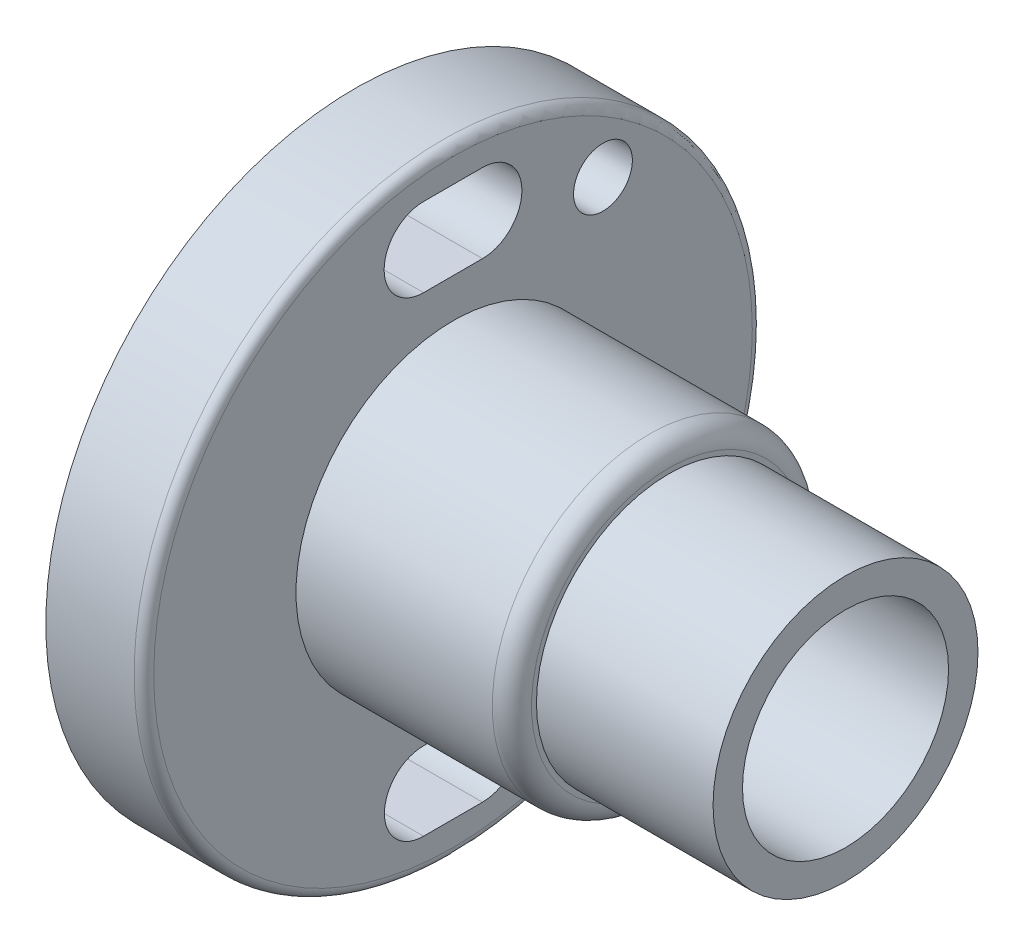
SolidWorks part; units mm, degrees
ref_plane "Front Plane" through (0, 0, 0) normal (0, 0, 1) x (1, 0, 0)
ref_plane "Top Plane" through (0, 0, 0) normal (0, 1, 0) x (1, 0, 0)
ref_plane "Right Plane" through (0, 0, 0) normal (1, 0, 0) x (0, 0, -1)
sketch "Sketch1" plane through (0, 0, 0) normal (1, 0, 0) x (0, 0, -1)
  circle A0 centre (0, 0) radius 31.5
  dimension "D1" = 63
extrude "Boss-Extrude1" add sketch "Sketch1" along normal blind 10
sketch "Sketch2" plane through (10, 0, 0) normal (1, 0, 0) x (0, 0, -1)
  circle A0 centre (0, 0) radius 16
extrude "Boss-Extrude2" add sketch "Sketch2" along normal blind 22
sketch "Sketch3" plane through (32, 0, 0) normal (1, 0, 0) x (0, 0, -1)
  circle A0 centre (0, 0) radius 13.5
extrude "Boss-Extrude3" add sketch "Sketch3" along normal blind 18
fillet "Fillet1" radius 1 1 edges at (10, 0, -31.5)
fillet "Fillet6" radius 2 1 edges at (32, 0, -16)
sketch "Sketch4" plane through (0, 0, 0) normal (-1, 0, 0) x (0, 0, 1)
  circle A0 centre (0, 0) radius 10.5
extrude "Cut-Extrude1" cut sketch "Sketch4" against normal blind 150
sketch "Sketch5" plane through (0, 0, 0) normal (-1, 0, 0) x (0, 0, 1)
  circle A0 centre (0, 0) radius 12.7
extrude "Cut-Extrude2" cut sketch "Sketch5" against normal blind 23.5
sketch "Sketch6" plane through (0, 0, 0) normal (-1, 0, 0) x (0, 0, 1)
  circle A0 centre (0, 0) radius 13.95
extrude "Cut-Extrude3" cut sketch "Sketch6" against normal blind 17.7
sketch "Sketch7" plane through (0, 0, 0) normal (-1, 0, 0) x (0, 0, 1)
  circle A1 centre (0, 0) radius 14.5
extrude "Cut-Extrude4" cut sketch "Sketch7" against normal blind 15.5
sketch "Sketch8" plane through (0, 0, 0) normal (-1, 0, 0) x (0, 0, 1)
  circle A1 centre (0, 0) radius 16
extrude "Cut-Extrude5" cut sketch "Sketch8" against normal blind 5.5
sketch "Sketch9" plane through (0, 0, 0) normal (-1, 0, 0) x (0, 0, 1)
  circle A1 centre (0, 0) radius 19.5
extrude "Cut-Extrude6" cut sketch "Sketch9" against normal blind 2.5
sketch "Sketch10" plane through (10, 0, 0) normal (1, 0, 0) x (0, 0, -1)
  line L0 (0, 34.9606) -> (0, -36.0362) construction
  line L1 (36.33, 0) -> (-43.4996, 0) construction
  line L2 (20.5493, 28.2837) -> (12.4123, 17.084) construction
  line L3 (19.9066, -27.3991) -> (0, 0) construction
  circle A0 centre (0, 0) radius 26 construction
  arc A1 (0, 34.9606) -> (20.5493, 28.2837) centre (0, 0) cw
  circle A2 centre (15.28, 21.0311) radius 3
  arc A3 (0, -33.8671) -> (19.9066, -27.3991) centre (0, 0) ccw
  circle A4 centre (15.2824, -21.0344) radius 3
extrude "Cut-Extrude11" cut sketch "Sketch10" against normal blind 20 contours A2
sketch "Sketch11" plane through (0, 0, 0) normal (-1, 0, 0) x (0, 0, 1)
  line L0 (-21.1603, -29.1246) -> (0, 0) construction
  line L1 (0, 34.9601) -> (0, -36.0357) construction
  line L3 (-42.0485, 0) -> (41.1098, 0) construction
  arc A0 (0, -36) -> (-21.1603, -29.1246) centre (0, 0) cw
  circle A1 centre (0, 0) radius 26 construction
  circle A2 centre (-15.2824, -21.0344) radius 3
extrude "Cut-Extrude12" cut sketch "Sketch11" against normal blind 20 contours A2
sketch "Sketch12" plane through (0, 0, 0) normal (-1, 0, 0) x (0, 0, 1)
  line L0 (0, 40.2488) -> (0, -43.5872) construction
  line L1 (-43.4622, 0) -> (44.4468, 0) construction
  line L2 (0, 0) -> (0, -24)
  line L3 (-3, -24) -> (3, -24) construction
  line L4 (-3, -20.0092) -> (3, -20.0092)
  line L5 (-3, -20) -> (3, -20)
  line L6 (-3, -28) -> (3, -28)
  line L7 (-3, -27.9908) -> (3, -27.9908)
  arc A0 (-3, -20.0092) -> (-3, -27.9908) centre (-3, -24) ccw
  arc A3 (3, -27.9908) -> (3, -20.0092) centre (3, -24) ccw
  point P16 (0, -24)
extrude "Cut-Extrude16" cut sketch "Sketch12" against normal blind 20
sketch "Sketch14" plane through (0, 0, 0) normal (-1, 0, 0) x (0, 0, 1)
  line L0 (0, 36.597) -> (0, -36.9115) construction
  line L1 (-38.7699, 0) -> (39.0651, 0) construction
  line L5 (-3, 24) -> (3, 24) construction
  line L6 (-3, 28.0208) -> (3, 28.0208)
  line L7 (-3, 19.9792) -> (3, 19.9792)
  arc A2 (-3, 28.0208) -> (-3, 19.9792) centre (-3, 24) ccw
  arc A3 (3, 19.9792) -> (3, 28.0208) centre (3, 24) ccw
  point P8 (0, 24)
extrude "Cut-Extrude17" cut sketch "Sketch14" against normal blind 20
